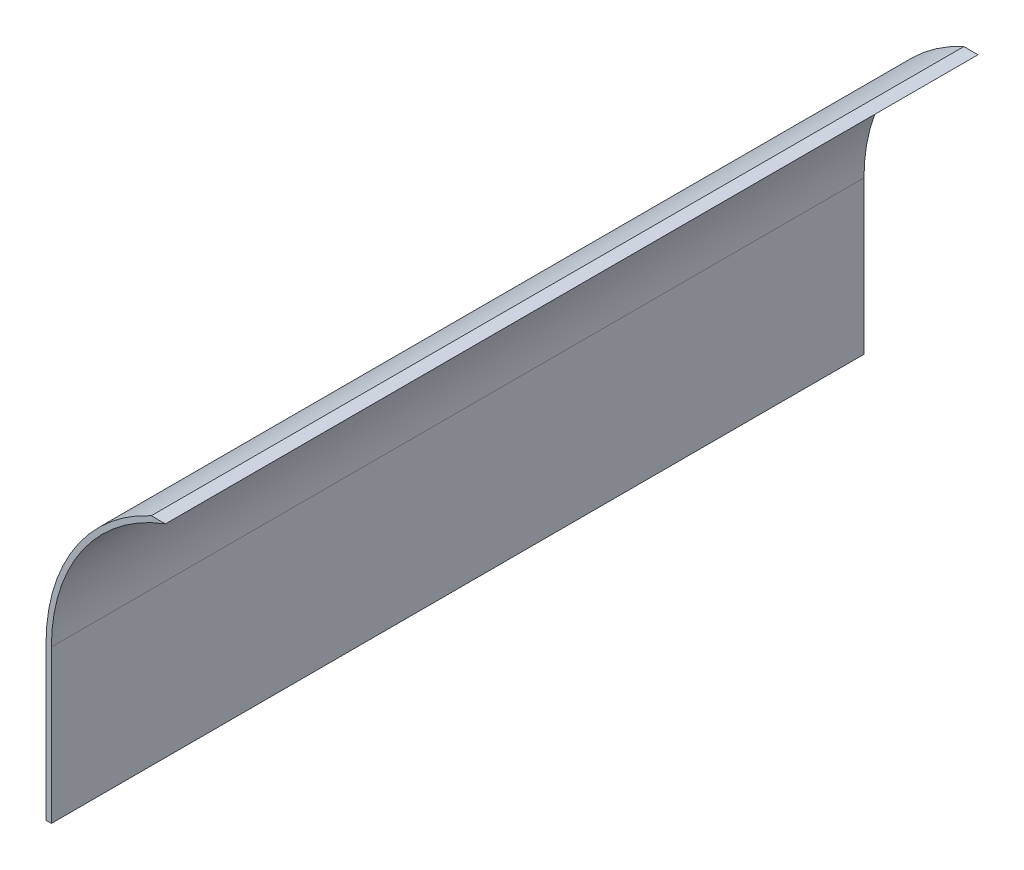
SolidWorks part; units mm, degrees
ref_plane "Front Plane" through (0, 0, 0) normal (0, 0, 1) x (1, 0, 0)
ref_plane "Top Plane" through (0, 0, 0) normal (0, 1, 0) x (1, 0, 0)
ref_plane "Right Plane" through (0, 0, 0) normal (1, 0, 0) x (0, 0, -1)
sketch "Sketch1" plane through (0, 0, 0) normal (0, 0, 1) x (1, 0, 0)
  line L7 (185, -185) -> (-185, -185)
  line L8 (185, -185) -> (185, 185)
  line L9 (185, 185) -> (-185, 185)
  line L10 (-185, -185) -> (-185, 185)
  line L11 (185, -185) -> (-185, 185) construction
  line L12 (185, 185) -> (-185, -185) construction
  point P0 (0, 0)
  point P6 (0, 0)
  dimension "D3" = 370
  dimension "D4" = 370
extrude "Boss-Extrude1" add sketch "Sketch1" along normal mid plane 2000
fillet "Fillet1" radius 100 4 edges at (185, 185, 0) (-185, -185, 0) (185, -185, 0) (-185, 185, 0)
shell "Shell1" thickness 3
sketch "Sketch2" plane through (0, 0, 1000) normal (0, 0, 1) x (1, 0, 0)
  line L0 (85, 185) -> (-85, 185) construction
  line L1 (0, 185) -> (241.7348, 185)
  line L2 (0, 185) -> (0, -209.7612)
  line L3 (0, -209.7612) -> (241.7348, -209.7612)
  line L4 (241.7348, 185) -> (241.7348, -209.7612)
extrude "Cut-Extrude1" cut sketch "Sketch2" against normal through all
sketch "Sketch3" plane through (-182, 0, 0) normal (1, 0, 0) x (0, 0, -1)
  line L1 (1000, 85) -> (1000, -85) construction
  line L2 (-1348.1285, 581.9659) -> (548, 581.9659)
  line L3 (-1348.1285, 581.9659) -> (-1348.1285, -718.3204)
  line L4 (-1348.1285, -718.3204) -> (548, -718.3204)
  line L6 (548, 581.9659) -> (548, -718.3204)
  dimension "D1" = 452
extrude "Cut-Extrude2" cut sketch "Sketch3" against normal through all and the other way through all
sketch "Sketch4" plane through (-185, 0, 0) normal (-1, 0, 0) x (0, 0, 1)
  line L0 (-1000, 85) -> (-1000, -85) construction
  line L1 (-1000, 0) -> (-463.3989, 0)
  line L2 (-1000, 0) -> (-1000, -206.2476)
  line L3 (-1000, -206.2476) -> (-463.3989, -206.2476)
  line L4 (-463.3989, 0) -> (-463.3989, -206.2476)
sketch "Sketch5" plane through (-185, 0, 0) normal (-1, 0, 0) x (0, 0, 1)
  line L0 (-1000, 0) -> (-463.3989, 0) construction
  line L5 (-427.7201, 176) -> (-1097.1047, -176) construction
  line L6 (-427.7201, -176) -> (-1097.1047, 176) construction
  line L8 (-1097.1047, 176) -> (-427.7201, 176)
  line L9 (-1097.1047, 176) -> (-1097.1047, 220.432)
  line L10 (-1097.1047, 220.432) -> (-427.7201, 220.432)
  line L11 (-427.7201, 176) -> (-427.7201, 220.432)
  line L12 (-1097.1047, -176) -> (-427.7201, -176)
  line L13 (-1097.1047, -176) -> (-1097.1047, -238.8446)
  line L14 (-1097.1047, -238.8446) -> (-427.7201, -238.8446)
  line L15 (-427.7201, -176) -> (-427.7201, -238.8446)
  point P0 (-762.4124, 0)
  dimension "D1" = 352
extrude "Cut-Extrude4" cut sketch "Sketch5" against normal through all
extrude "Cut-Extrude5" cut sketch "Sketch4" against normal through all
